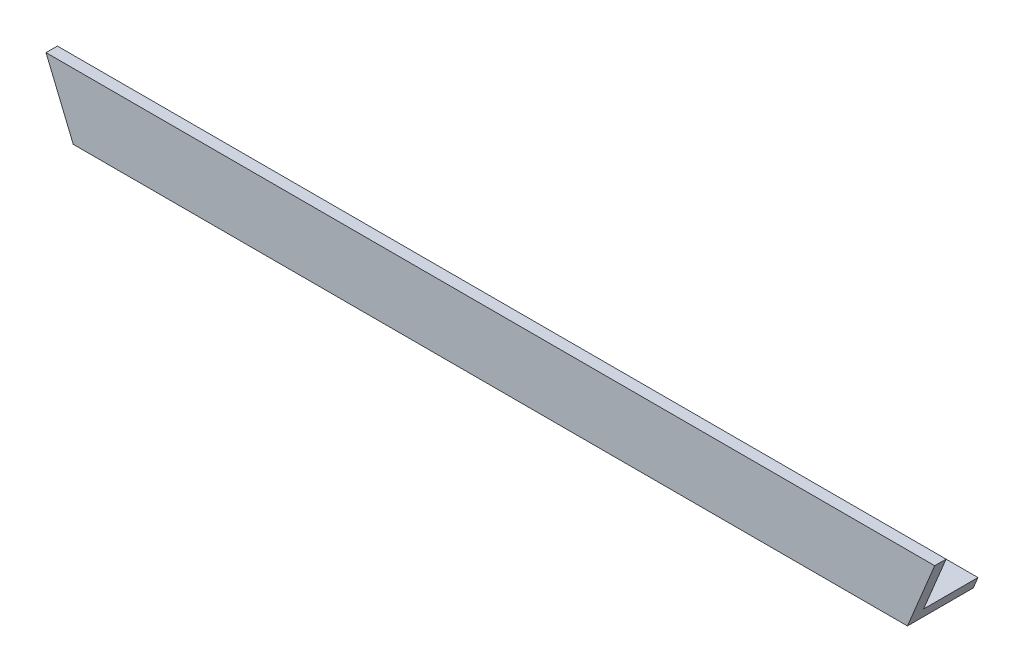
SolidWorks part; units mm, degrees
ref_plane "Front Plane" through (0, 0, 0) normal (0, 0, 1) x (1, 0, 0)
ref_plane "Top Plane" through (0, 0, 0) normal (0, 1, 0) x (1, 0, 0)
ref_plane "Right Plane" through (0, 0, 0) normal (1, 0, 0) x (0, 0, -1)
sketch "Sketch1" plane through (0, 0, 0) normal (1, 0, 0) x (0, 0, -1)
  line L0 (0, 0) -> (20, 0)
  line L1 (20, 0) -> (20, 3.4612)
  line L2 (20, 3.4612) -> (3.4612, 3.4612)
  line L3 (3.4612, 3.4612) -> (3.4612, 20)
  line L4 (3.4612, 20) -> (0, 20)
  line L5 (0, 20) -> (0, 0)
  dimension "D1" = 3.4612
  dimension "D2" = 20
extrude "Boss-Extrude1" add sketch "Sketch1" along normal blind 270
sketch "Sketch2" plane through (0, 0, 0) normal (0, 0, -1) x (1, 0, 0)
  line L7 (270, -20) -> (270, 0)
  line L9 (0, -20) -> (0, 0)
  line L10 (0, -20) -> (8.2843, 0)
  line L11 (270, 0) -> (0, 0) construction
  line L12 (8.2843, 0) -> (0, 0)
  line L13 (270, -20) -> (261.7157, 0)
  line L14 (261.7157, 0) -> (270, 0)
  dimension "D1" = 22.5
extrude "Cut-Extrude1" cut sketch "Sketch2" along normal through all
